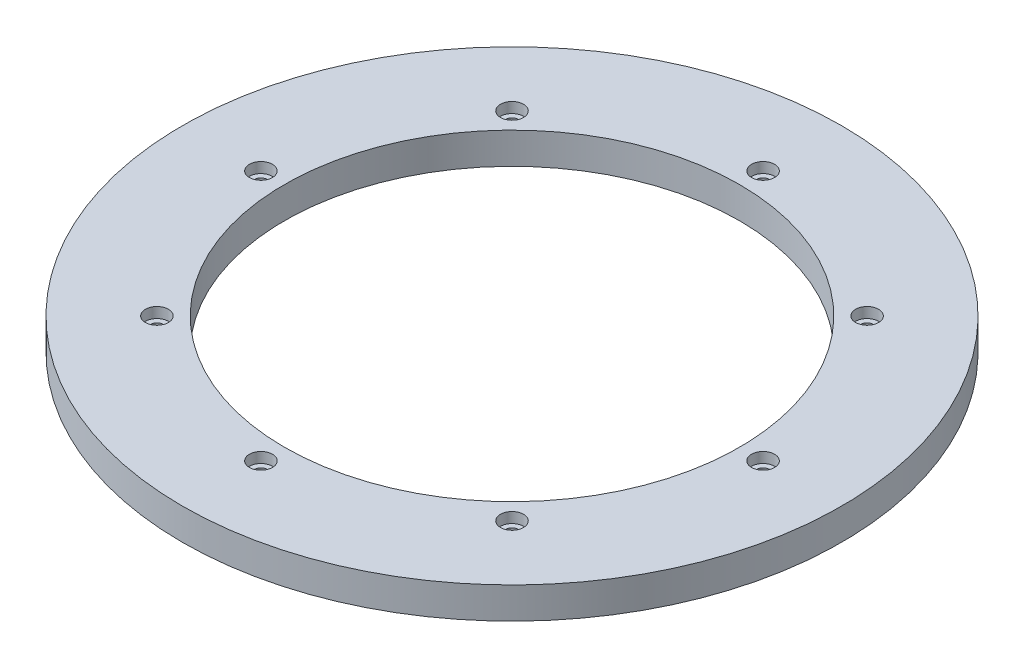
SolidWorks part; units mm, degrees
ref_plane "Front Plane" through (0, 0, 0) normal (0, 0, 1) x (1, 0, 0)
ref_plane "Top Plane" through (0, 0, 0) normal (0, 1, 0) x (1, 0, 0)
ref_plane "Right Plane" through (0, 0, 0) normal (1, 0, 0) x (0, 0, -1)
sketch "Sketch1" plane through (0, 0, 0) normal (1, 0, 0) x (0, 0, -1)
  line L0 (0, -1000) -> (0, 49000) construction
  line L12 (-315, 14.606) -> (-315, 44.606)
  line L21 (-217.5, 44.606) -> (-217.5, 14.606)
  line L22 (-315, 44.606) -> (-217.5, 44.606)
  line L23 (-315, 14.606) -> (-217.5, 14.606)
  dimension "D1" = 30
revolve "Revolve1" add sketch "Sketch1" angle 360 about L0
sketch "Sketch2" plane through (0, 44.606, 0) normal (0, 1, 0) x (1, 0, 0)
  line L0 (0, -1000) -> (0, 49000) construction
  line L1 (-1000, 0) -> (49000, 0) construction
  circle A0 centre (0, 240) radius 11
  circle A1 centre (169.7056, 169.7056) radius 11
  circle A2 centre (240, 0) radius 11
  circle A3 centre (169.7056, -169.7056) radius 11
  circle A4 centre (0, -240) radius 11
  circle A5 centre (-169.7056, -169.7056) radius 11
  circle A6 centre (-240, 0) radius 11
  circle A7 centre (-169.7056, 169.7056) radius 11
  point P23 (0, 0)
  dimension "D1" = 240
  dimension "D2" = 22
  dimension "D3" = 8
extrude "Cut-Extrude1" cut sketch "Sketch2" against normal blind 10
sketch "Sketch3" plane through (0, 44.606, 0) normal (0, 1, 0) x (1, 0, 0)
  line L0 (0, -1000) -> (0, 49000) construction
  line L1 (-1000, 0) -> (49000, 0) construction
  circle A0 centre (0, 240) radius 6
  circle A1 centre (169.7056, 169.7056) radius 6
  circle A2 centre (240, 0) radius 6
  circle A3 centre (169.7056, -169.7056) radius 6
  circle A4 centre (0, -240) radius 6
  circle A5 centre (-169.7056, -169.7056) radius 6
  circle A6 centre (-240, 0) radius 6
  circle A7 centre (-169.7056, 169.7056) radius 6
  point P25 (0, 0)
  dimension "D1" = 240
  dimension "D2" = 12
  dimension "D3" = 8
extrude "Cut-Extrude2" cut sketch "Sketch3" against normal through all
